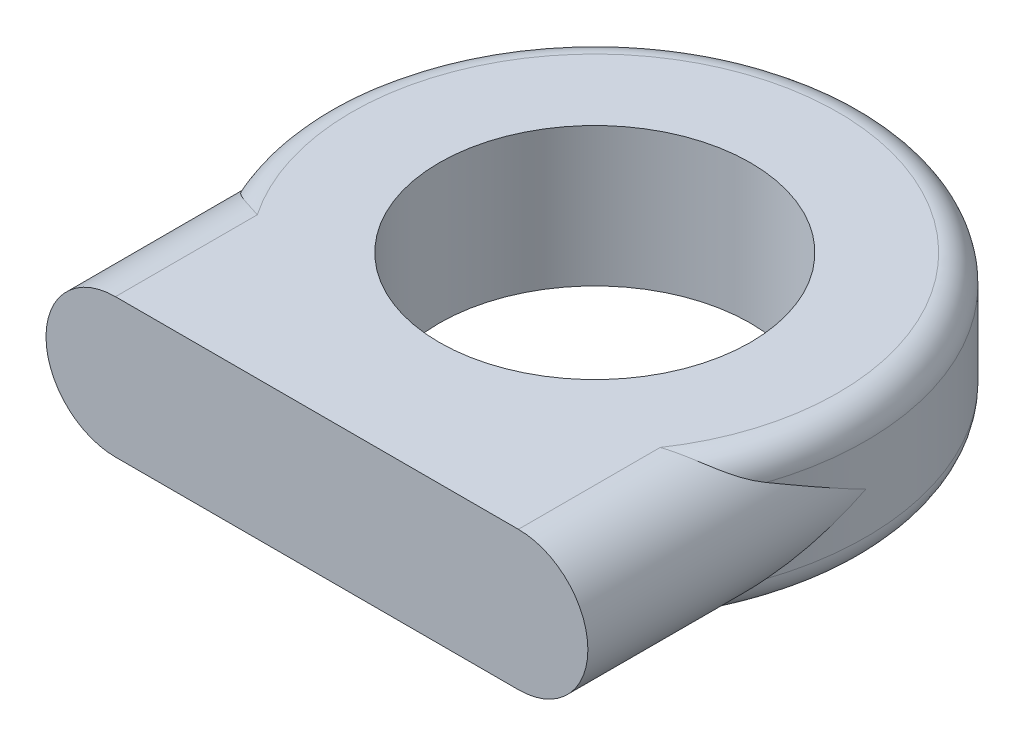
SolidWorks part; units mm, degrees
ref_plane "前视基准面" through (0, 0, 0) normal (0, 0, 1) x (1, 0, 0)
ref_plane "上视基准面" through (0, 0, 0) normal (0, 1, 0) x (1, 0, 0)
ref_plane "右视基准面" through (0, 0, 0) normal (1, 0, 0) x (0, 0, -1)
other "Configuration Table"
sketch "草图1" plane through (0, 0, 0) normal (0, 0, 1) x (1, 0, 0)
  line L0 (-7.25, 0) -> (7.25, 0) construction
  line L1 (-7.25, 2.5) -> (7.25, 2.5)
  line L2 (-7.25, -2.5) -> (7.25, -2.5)
  arc A0 (-7.25, 2.5) -> (-7.25, -2.5) centre (-7.25, 0) ccw
  arc A1 (7.25, -2.5) -> (7.25, 2.5) centre (7.25, 0) ccw
  point P2 (0, 0)
  dimension "D1" = 5
  dimension "D2" = 14.5
extrude "凸台-拉伸1" add sketch "草图1" along normal blind 10 contours A1 L1 A0 L2
sketch "草图2" plane through (0, 2.5, 0) normal (0, 1, 0) x (1, 0, 0)
  circle A0 centre (0, 0) radius 9.75
extrude "凸台-拉伸2" add sketch "草图2" against normal blind 5
fillet "圆角2" radius 1 2 edges at (0, -2.5, -9.75) (0, 2.5, -9.75)
sketch "草图3" plane through (0, 2.5, 0) normal (0, 1, 0) x (1, 0, 0)
  circle A0 centre (0, 0) radius 5.6
  dimension "D1" = 11.2
extrude "切除-拉伸1" cut sketch "草图3" against normal blind 5 contours A0
equation "\"2、15\"=10.5109"
